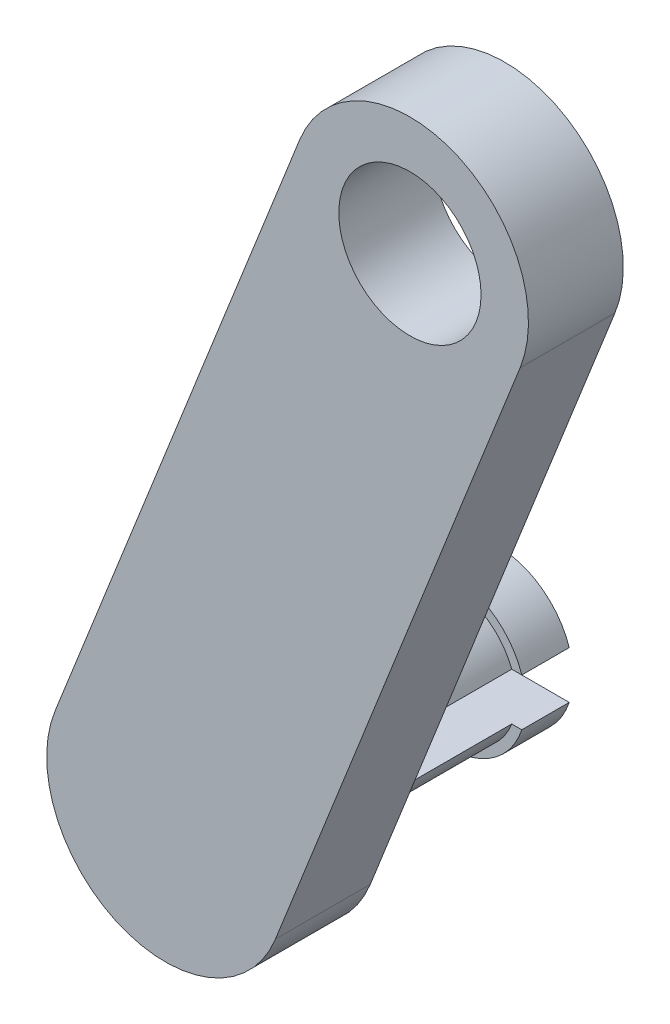
SolidWorks part; units mm, degrees
ref_plane "Plan de face" through (0, 0, 0) normal (0, 0, 1) x (1, 0, 0)
ref_plane "Plan de dessus" through (0, 0, 0) normal (0, 1, 0) x (1, 0, 0)
ref_plane "Plan de droite" through (0, 0, 0) normal (1, 0, 0) x (0, 0, -1)
sketch "Esquisse1" plane through (0, 0, 0) normal (0, 0, 1) x (1, 0, 0)
  line L0 (-16, -1) -> (-21.1599, -14.0144) construction
  line L1 (-13.676, -1.9214) -> (-18.8359, -14.9359)
  line L2 (-18.324, -0.0786) -> (-23.4839, -13.093)
  arc A0 (-13.676, -1.9214) -> (-18.324, -0.0786) centre (-16, -1) ccw
  arc A1 (-23.4839, -13.093) -> (-18.8359, -14.9359) centre (-21.1599, -14.0144) ccw
  point P4 (-18.5799, -7.5072)
  dimension "D1" = 5
extrude "Boss.-Extru.1" add sketch "Esquisse1" along normal blind 2
sketch "Esquisse2" plane through (0, 0, 2) normal (0, 0, 1) x (1, 0, 0)
  circle A0 centre (-16, -1) radius 1.5
  dimension "D1" = 3
extrude "Enlèv. mat.-Extru.1" cut sketch "Esquisse2" against normal blind 3
sketch "Esquisse3" plane through (0, 0, 0) normal (0, 0, -1) x (-1, 0, 0)
  circle A0 centre (21.1599, -14.0144) radius 1.4
  dimension "D1" = 2.8
extrude "Boss.-Extru.2" add sketch "Esquisse3" along normal blind 4
sketch "Esquisse4" plane through (0, 0, -4) normal (0, 0, -1) x (-1, 0, 0)
  circle A0 centre (21.1599, -14.0144) radius 1.6
  dimension "D1" = 3.2
extrude "Boss.-Extru.3" add sketch "Esquisse4" along normal blind 1
sketch "Esquisse5" plane through (0, 0, -5) normal (0, 0, -1) x (-1, 0, 0)
  line L1 (19.1599, -13.5144) -> (23.1599, -13.5144)
  line L2 (19.1599, -13.5144) -> (19.1599, -14.5144)
  line L3 (19.1599, -14.5144) -> (23.1599, -14.5144)
  line L4 (23.1599, -13.5144) -> (23.1599, -14.5144)
  point P4 (23.1599, -14.0144)
  dimension "D1" = 0.5
  dimension "D2" = 0.5
  dimension "D3" = 4
  dimension "D4" = 2
extrude "Enlèv. mat.-Extru.2" cut sketch "Esquisse5" against normal blind 5
